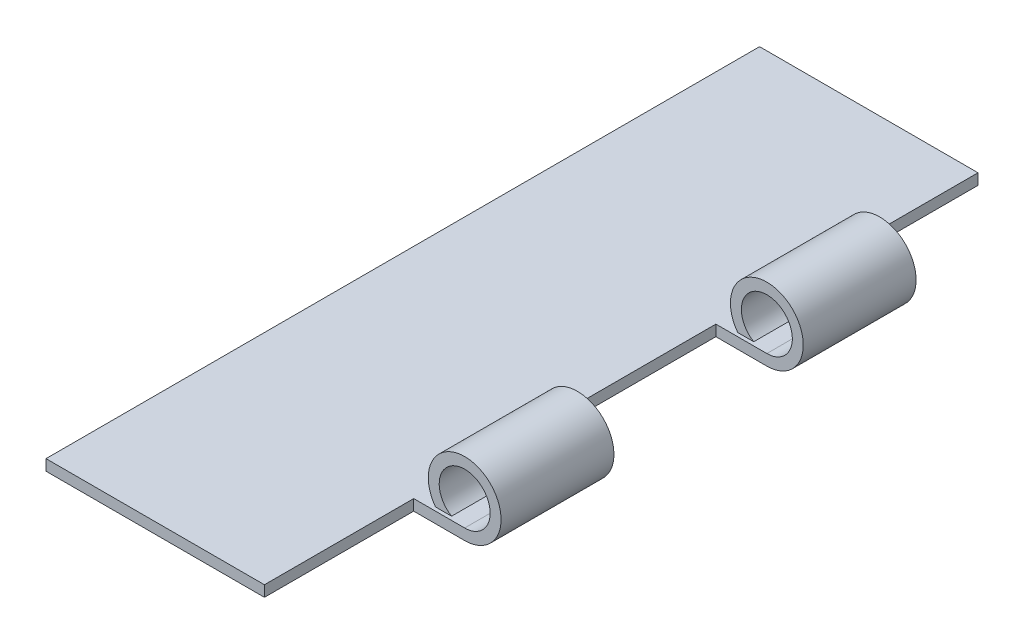
SolidWorks part; units mm, degrees
material "AISI 316 Stainless Steel Sheet (SS)"
ref_plane "Front Plane" through (0, 0, 0) normal (0, 0, 1) x (1, 0, 0)
ref_plane "Top Plane" through (0, 0, 0) normal (0, 1, 0) x (1, 0, 0)
ref_plane "Right Plane" through (0, 0, 0) normal (1, 0, 0) x (0, 0, -1)
sketch "Sketch1" plane through (0, 0, 0) normal (0, 0, 1) x (1, 0, 0)
  line L0 (0, 0) -> (30, 0)
  line L1 (30, 0) -> (32, 0)
  line L2 (32, 0) -> (37, 0)
  line L3 (37, 0) -> (37, 5) construction
  line L4 (33, 2) -> (35.1972, 2)
  line L5 (0, 1.5) -> (30, 1.5)
  line L6 (30, 1.5) -> (32, 1.5)
  line L7 (32, 1.5) -> (37, 1.5)
  line L8 (32, 2) -> (37, 2) construction
  line L9 (0, 1.5) -> (0, 0)
  arc A0 (37, 0) -> (33, 2) centre (37, 5) ccw
  arc A1 (37, 1.5) -> (35.1972, 2) centre (37, 5) ccw
  circle A2 centre (37, 5) radius 3.5 construction
  circle A3 centre (37, 5) radius 5 construction
  dimension "D1" = 30
  dimension "D2" = 2
  dimension "D3" = 5
  dimension "D4" = 5
  dimension "D5" = 2
  dimension "D6" = 1.5
extrude "Boss-Extrude1" add sketch "Sketch1" along normal blind 98
sketch "Sketch2" plane through (0, 0, 0) normal (0, -1, 0) x (1, 0, 0)
  line L0 (0, 0) -> (30, 0) construction
  line L2 (30, 0) -> (30, 15.5) construction
  line L3 (30, 0) -> (32, 0) construction
  line L4 (30, 15.5) -> (30, 41)
  line L5 (30, 15.5) -> (50.1658, 15.5)
  line L6 (50.1658, 15.5) -> (50.1658, 41)
  line L7 (50.1658, 41) -> (30, 41)
  line L8 (30, 98) -> (30, 82.5) construction
  line L9 (0, 98) -> (37, 98) construction
  line L11 (30, 82.5) -> (50.1658, 82.5)
  line L12 (30, 82.5) -> (30, 57)
  line L13 (30, 57) -> (50.1658, 57)
  line L14 (50.1658, 82.5) -> (50.1658, 57)
  line L15 (30, 0) -> (50.1658, 0)
  line L16 (30, 0) -> (30, 15.5)
  line L17 (30, 15.5) -> (50.1658, 15.5)
  line L18 (50.1658, 0) -> (50.1658, 15.5)
  line L19 (30, 82.5) -> (50.1658, 82.5)
  line L20 (30, 82.5) -> (30, 98)
  line L21 (30, 98) -> (50.1658, 98)
  line L22 (50.1658, 82.5) -> (50.1658, 98)
  line L23 (30, 41) -> (50.1658, 41)
  line L24 (30, 41) -> (30, 57)
  line L25 (30, 57) -> (50.1658, 57)
  line L26 (50.1658, 41) -> (50.1658, 57)
  line M1 (0, 0) -> (37, 0)
  line M2 (37, 0) -> (37, 98)
  line M3 (37, 98) -> (0, 98)
  dimension "D1" = 15.5
  dimension "D2" = 25.5
  dimension "D3" = 25.5
  dimension "D4" = 15.5
extrude "Cut-Extrude1" cut sketch "Sketch2" against normal through all contours L24 L7 L13 M2 | L7 L26 L13 M2 | L16 L5 M1 M2 | L15 L18 L5 M2 | L20 L11 M2 M3 | L11 L22 L21 M2
sketch "Sketch4" plane through (0, 0, 82.5) normal (0, 0, 1) x (1, 0, 0)
  line L1 (30, 0) -> (42.7464, 0)
  line L2 (30, 0) -> (30, 11.4247)
  line L3 (30, 11.4247) -> (42.7464, 11.4247)
  line L4 (42.7464, 0) -> (42.7464, 11.4247)
extrude "Cut-Extrude3" cut sketch "Sketch4" against normal blind 5
sketch "Sketch5" plane through (0, 0, 57) normal (0, 0, -1) x (-1, 0, 0)
  line L1 (-30, 0) -> (-45.0196, 0)
  line L2 (-30, 0) -> (-30, 11.204)
  line L3 (-30, 11.204) -> (-45.0196, 11.204)
  line L4 (-45.0196, 0) -> (-45.0196, 11.204)
extrude "Cut-Extrude4" cut sketch "Sketch5" against normal blind 5
sketch "Sketch6" plane through (0, 0, 41) normal (0, 0, 1) x (1, 0, 0)
  line L1 (30, 0) -> (43.7952, 0)
  line L2 (30, 0) -> (30, 11.126)
  line L3 (30, 11.126) -> (43.7952, 11.126)
  line L4 (43.7952, 0) -> (43.7952, 11.126)
extrude "Cut-Extrude5" cut sketch "Sketch6" against normal blind 5
sketch "Sketch7" plane through (0, 0, 15.5) normal (0, 0, -1) x (-1, 0, 0)
  line L1 (-30, 0) -> (-43.6887, 0)
  line L2 (-30, 0) -> (-30, 12.1956)
  line L3 (-30, 12.1956) -> (-43.6887, 12.1956)
  line L4 (-43.6887, 0) -> (-43.6887, 12.1956)
extrude "Cut-Extrude6" cut sketch "Sketch7" against normal blind 5
